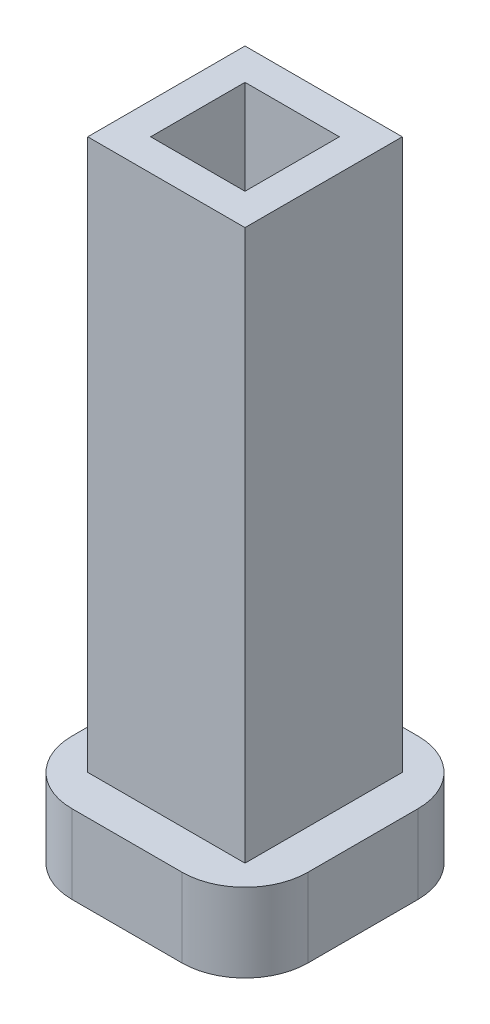
SolidWorks part; units mm, degrees
material "AISI 1010 Aço, barra laminada a quente"
ref_plane "Plano frontal" through (0, 0, 0) normal (0, 0, 1) x (1, 0, 0)
ref_plane "Plano superior" through (0, 0, 0) normal (0, 1, 0) x (1, 0, 0)
ref_plane "Plano direito" through (0, 0, 0) normal (1, 0, 0) x (0, 0, -1)
sketch "Esboço2" plane through (0, 0, 0) normal (0, 1, 0) x (1, 0, 0)
  line L1 (0, 0) -> (15, 0)
  line L2 (0, 0) -> (0, -15)
  line L3 (0, -15) -> (15, -15)
  line L4 (15, 0) -> (15, -15)
  dimension "D1" = 15
  dimension "D2" = 15
extrude "Ressalto-extrusão2" add sketch "Esboço2" along normal blind 5
sketch "Esboço3" plane through (0, 5, 0) normal (0, 1, 0) x (1, 0, 0)
  line L0 (0, 0) -> (0, -15) construction
  line L1 (2.5, -2.5) -> (12.5, -2.5)
  line L2 (2.5, -2.5) -> (2.5, -12.5)
  line L3 (2.5, -12.5) -> (12.5, -12.5)
  line L4 (12.5, -2.5) -> (12.5, -12.5)
  line L5 (15, 0) -> (0, 0) construction
  dimension "D1" = 10
  dimension "D2" = 10
  dimension "D3" = 2.5
  dimension "D4" = 2.5
extrude "Ressalto-extrusão3" add sketch "Esboço3" along normal blind 35
fillet "Filete1" radius 4 4 edges at (0, 2.5, 15) (15, 2.5, 15) (15, 2.5, 0) (0, 2.5, 0)
sketch "Esboço4" plane through (0, 40, 0) normal (0, 1, 0) x (1, 0, 0)
  line L0 (12.5, -2.5) -> (2.5, -2.5) construction
  line L1 (4.5, -4.5) -> (10.5, -4.5)
  line L2 (4.5, -4.5) -> (4.5, -10.5)
  line L3 (4.5, -10.5) -> (10.5, -10.5)
  line L4 (10.5, -4.5) -> (10.5, -10.5)
  line L5 (2.5, -2.5) -> (2.5, -12.5) construction
  dimension "D1" = 6
  dimension "D2" = 6
  dimension "D3" = 2
  dimension "D4" = 2
extrude "Corte-extrusão1" cut sketch "Esboço4" against normal through all
